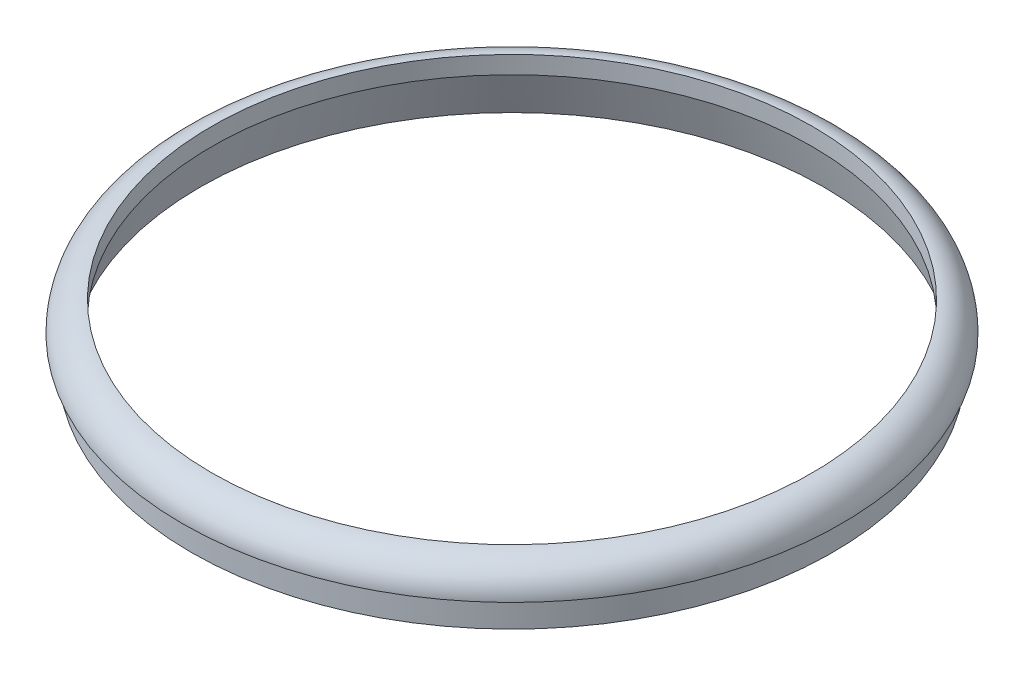
SolidWorks part; units mm, degrees
material "ABS"
ref_plane "Front Plane" through (0, 0, 0) normal (0, 0, 1) x (1, 0, 0)
ref_plane "Top Plane" through (0, 0, 0) normal (0, 1, 0) x (1, 0, 0)
ref_plane "Right Plane" through (0, 0, 0) normal (1, 0, 0) x (0, 0, -1)
sketch "Sketch1" plane through (0, 0, 0) normal (0, 0, 1) x (1, 0, 0)
  line L1 (135.0962, 0) -> (138.9062, 0)
  line L2 (138.9062, 0) -> (138.9062, 12.7)
  line L3 (138.9062, 12.7) -> (142.7163, 12.7)
  line L5 (0, 164.3885) -> (0, -19.9978)
  line L7 (130.0163, 25.4) -> (130.0163, 17.78)
  line L8 (130.0163, 17.78) -> (135.0962, 0)
  arc A0 (142.7163, 12.7) -> (130.0163, 25.4) centre (130.0163, 12.7) ccw
  point P9 (0, 72.1954)
  dimension "D7" = 12.7
  dimension "D8" = 18.4915
  dimension "D1" = 12.7
  dimension "D2" = 12.7
  dimension "D3" = 3.81
  dimension "D4" = 3.81
  dimension "D5" = 138.9062
  dimension "D6" = 12.7
revolve "Revolve1" add sketch "Sketch1" angle 360 about L5
